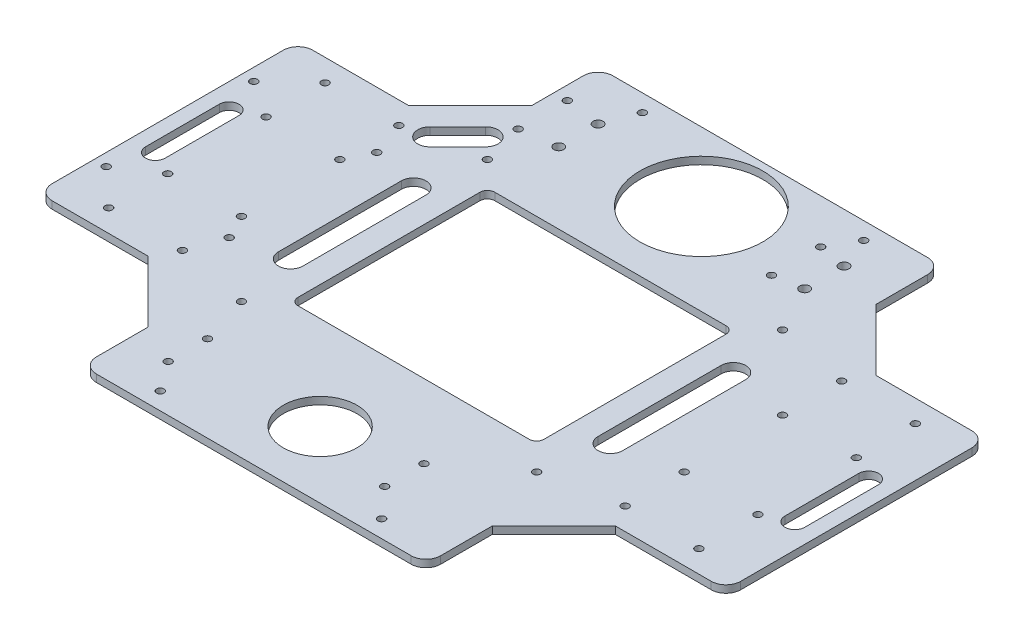
SolidWorks part; units mm, degrees
material "Thornel Mat VMA"
ref_plane "前视基准面" through (0, 0, 0) normal (0, 0, 1) x (1, 0, 0)
ref_plane "上视基准面" through (0, 0, 0) normal (0, 1, 0) x (1, 0, 0)
ref_plane "右视基准面" through (0, 0, 0) normal (1, 0, 0) x (0, 0, -1)
other "Configuration Table"
sketch "草图1" plane through (0, 0, 0) normal (0, 1, 0) x (1, 0, 0)
  line L0 (0, 0) -> (0, 105) construction
  line L1 (-140, -105) -> (140, -105)
  line L2 (-140, -105) -> (-140, 105)
  line L3 (-140, 105) -> (140, 105)
  line L4 (140, -105) -> (140, 105)
  line L5 (-140, -105) -> (140, 105) construction
  line L6 (-140, 105) -> (140, -105) construction
  line L7 (0, 0) -> (140, 0) construction
  line L8 (-70, 105) -> (-70, 53)
  line L9 (-70, 53) -> (-140, 53)
  line L10 (70, 53) -> (140, 53)
  line L11 (70, 105) -> (70, 53)
  line L12 (70, -53) -> (140, -53)
  line L13 (70, -105) -> (70, -53)
  line L14 (-70, -53) -> (-140, -53)
  line L15 (-70, -105) -> (-70, -53)
  point P0 (0, 0)
  dimension "D1" = 280
  dimension "D2" = 210
  dimension "D3" = 106
  dimension "D4" = 140
extrude "凸台-拉伸1" add sketch "草图1" along normal blind 3 contours L15 L1 L13 L12 L4 L10 L11 L3 L8 L9 L2 L14
sketch "草图2" plane through (0, 3, 0) normal (0, 1, 0) x (1, 0, 0)
  line L0 (0, 0) -> (140, 0) construction
  line L1 (140, -53) -> (140, 53) construction
  line L2 (0, 0) -> (0, 105) construction
  line L3 (-70, 105) -> (70, 105) construction
  line L4 (70, 53) -> (140, 53) construction
  circle A0 centre (120, 44) radius 1.5
  circle A1 centre (90, 44) radius 1.5
  circle A2 centre (90, 20) radius 1.5
  circle A3 centre (120, 20) radius 1.5
  circle A4 centre (120, -20) radius 1.5
  circle A5 centre (120, -44) radius 1.5
  circle A6 centre (90, -20) radius 1.5
  circle A7 centre (90, -44) radius 1.5
  circle A8 centre (-90, -44) radius 1.5
  circle A9 centre (-90, -20) radius 1.5
  circle A10 centre (-120, -44) radius 1.5
  circle A11 centre (-120, -20) radius 1.5
  circle A12 centre (-120, 20) radius 1.5
  circle A13 centre (-90, 20) radius 1.5
  circle A14 centre (-90, 44) radius 1.5
  circle A15 centre (-120, 44) radius 1.5
  dimension "D1" = 3
  dimension "D2" = 3
  dimension "D3" = 3
  dimension "D4" = 3
  dimension "D11" = 90
  dimension "D12" = 9
  dimension "D5" = 24
  dimension "D6" = 24
  dimension "D7" = 30
  dimension "D8" = 30
  dimension "D9" = 90
  dimension "D10" = 9
extrude "切除-拉伸1" cut sketch "草图2" against normal blind 3
sketch "草图3" plane through (0, 3, 0) normal (0, 1, 0) x (1, 0, 0)
  line L0 (-19.5, 0) -> (-19.5, 110.5115) construction
  line L1 (-19.5, 0) -> (140, 0) construction
  line L2 (140, -53) -> (140, 53) construction
  line L3 (-86.4083, 77) -> (47.4083, 77) construction
  line L4 (0, 0) -> (0, 108.4938) construction
  line L5 (-19.5, 0) -> (-19.5, -115.6254) construction
  line L6 (-115.1345, -78) -> (76.1345, -78) construction
  line L7 (0, 0) -> (0, -114.288) construction
  line L8 (-9.8, 0) -> (-9.8, -143.8511) construction
  circle A0 centre (-64.5, 87) radius 1.5
  circle A4 centre (-64.5, 67) radius 1.5
  circle A5 centre (0, 77) radius 25
  circle A11 centre (34.2, -70) radius 1.5
  circle A12 centre (34.2, -86) radius 1.5
  circle A15 centre (0, -78) radius 15
  circle A20 centre (-50, 85) radius 2
  circle A21 centre (-50, 69) radius 2
  circle A22 centre (50, 85) radius 2
  circle A23 centre (50, 69) radius 2
  circle A24 centre (38.5, 87) radius 1.5
  circle A25 centre (38.5, 67) radius 1.5
  circle A26 centre (-53.8, -86) radius 1.5
  circle A27 centre (-53.8, -70) radius 1.5
  point P13 (-19.5, 77)
  point P26 (-19.5, -78)
  dimension "D1" = 3
  dimension "D2" = 77
  dimension "D6" = 50
  dimension "D7" = 3
  dimension "D11" = 30
  dimension "D12" = 4
  dimension "D13" = 50
  dimension "D15" = 4
  dimension "D17" = 8
  dimension "D18" = 3
  dimension "D20" = 10
  dimension "D3" = 10
  dimension "D4" = 45
  dimension "D5" = 19.5
  dimension "D8" = 8
  dimension "D9" = 44
  dimension "D10" = 78
  dimension "D14" = 8
  dimension "D16" = 50
  dimension "D19" = 58
  dimension "D21" = 9.8
extrude "切除-拉伸2" cut sketch "草图3" against normal blind 10
sketch "草图4" plane through (0, 3, 0) normal (0, 1, 0) x (1, 0, 0)
  line L1 (-50, -40) -> (50, -40)
  line L2 (-50, -40) -> (-50, 40)
  line L3 (-50, 40) -> (50, 40)
  line L4 (50, -40) -> (50, 40)
  line L5 (-50, -40) -> (50, 40) construction
  line L6 (-50, 40) -> (50, -40) construction
  point P0 (0, 0)
  dimension "D1" = 100
  dimension "D2" = 80
extrude "切除-拉伸3" cut sketch "草图4" against normal blind 3
fillet "圆角2" radius 3 4 edges at (50, 1.5, 40) (-50, 1.5, 40) (50, 1.5, -40) (-50, 1.5, -40)
sketch "草图5" plane through (0, 3, 0) normal (0, 1, 0) x (1, 0, 0)
  line L0 (-160.9894, 0) -> (160.9894, 0) construction
  line L1 (0, -135.5009) -> (0, 135.5009) construction
  circle A1 centre (-60, 50) radius 1.5
  circle A2 centre (-45, 98) radius 1.5
  circle A3 centre (60, 50) radius 1.5
  circle A4 centre (45, 98) radius 1.5
  circle A10 centre (45, -98) radius 1.5
  circle A11 centre (60, -50) radius 1.5
  circle A12 centre (-45, -98) radius 1.5
  circle A13 centre (-60, -50) radius 1.5
  point P4 (0, 0)
  point P8 (0, 0)
  dimension "D2" = 3
  dimension "D7" = 3
  dimension "D3" = 60
  dimension "D5" = 50
  dimension "D8" = 45
  dimension "D9" = 98
extrude "切除-拉伸4" cut sketch "草图5" against normal blind 3
fillet "圆角3" radius 6 8 edges at (-70, 1.5, -105) (70, 1.5, -105) (140, 1.5, -53) (140, 1.5, 53) (-70, 1.5, 105) (70, 1.5, 105) (-140, 1.5, 53) (-140, 1.5, -53)
chamfer "倒角1" distance 25 angle 45 4 edges at (70, 1.5, 53) (-70, 1.5, 53) (70, 1.5, -53) (-70, 1.5, -53)
sketch "草图7" plane through (0, 3, 0) normal (0, 1, 0) x (1, 0, 0)
  line L0 (0, 0) -> (0, 142.9478) construction
  line L1 (0, 0) -> (-184.5222, 0) construction
  line L2 (-130, -15) -> (-130, 15) construction
  line L3 (-134, -15) -> (-134, 15)
  line L4 (-126, -15) -> (-126, 15)
  line L5 (-65, -25) -> (-65, 25) construction
  line L6 (-70, -25) -> (-70, 25)
  line L7 (-60, -25) -> (-60, 25)
  line L8 (130, -15) -> (130, 15) construction
  line L14 (-110, 0) -> (-110, 75.2826) construction
  line L15 (-79.6569, 46.3431) -> (-68.3431, 57.6569) construction
  line L16 (-83.1924, 49.8787) -> (-71.8787, 61.1924)
  line L17 (-76.1213, 42.8076) -> (-64.8076, 54.1213)
  line L19 (134, -15) -> (134, 15)
  line L20 (126, -15) -> (126, 15)
  line L21 (65, -25) -> (65, 25) construction
  line L22 (70, -25) -> (70, 25)
  line L23 (60, -25) -> (60, 25)
  arc A0 (-134, -15) -> (-126, -15) centre (-130, -15) ccw
  arc A1 (-126, 15) -> (-134, 15) centre (-130, 15) ccw
  arc A2 (-70, -25) -> (-60, -25) centre (-65, -25) ccw
  arc A3 (-60, 25) -> (-70, 25) centre (-65, 25) ccw
  circle A8 centre (-135, 30) radius 1.5
  circle A9 centre (-85, 30) radius 1.5
  circle A10 centre (-85, -30) radius 1.5
  circle A11 centre (-135, -30) radius 1.5
  arc A12 (-83.1924, 49.8787) -> (-76.1213, 42.8076) centre (-79.6569, 46.3431) ccw
  arc A13 (-64.8076, 54.1213) -> (-71.8787, 61.1924) centre (-68.3431, 57.6569) ccw
  arc A16 (134, -15) -> (126, -15) centre (130, -15) cw
  arc A17 (126, 15) -> (134, 15) centre (130, 15) cw
  arc A18 (70, -25) -> (60, -25) centre (65, -25) cw
  arc A19 (60, 25) -> (70, 25) centre (65, 25) cw
  point P6 (-130, 0)
  point P13 (-65, 0)
  point P20 (130, 0)
  point P27 (65, 0)
  point P44 (-74, 52)
  dimension "D2" = 4
  dimension "D5" = 5
  dimension "D8" = 3
  dimension "D10" = 30
  dimension "D12" = 5
  dimension "D1" = 30
  dimension "D3" = 130
  dimension "D4" = 50
  dimension "D6" = 65
  dimension "D7" = 110
  dimension "D9" = 25
  dimension "D11" = 16
  dimension "D13" = 45
  dimension "D14" = 52
  dimension "D15" = 74
extrude "切除-拉伸6" cut sketch "草图7" against normal blind 10
